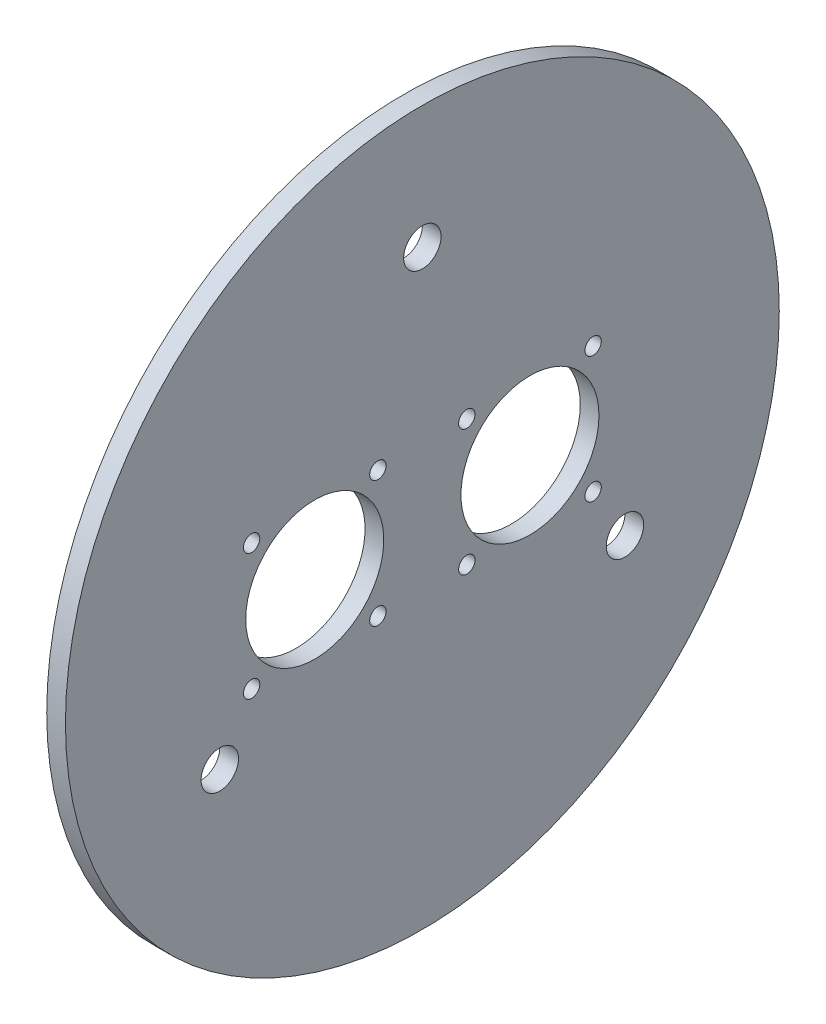
SolidWorks part; units mm, degrees
ref_plane "Front Plane" through (0, 0, 0) normal (0, 0, 1) x (1, 0, 0)
ref_plane "Top Plane" through (0, 0, 0) normal (0, 1, 0) x (1, 0, 0)
ref_plane "Right Plane" through (0, 0, 0) normal (1, 0, 0) x (0, 0, -1)
sketch "Sketch1" plane through (0, 0, 0) normal (1, 0, 0) x (0, 0, -1)
  line L0 (0, -76.29) -> (0, 76.29) construction
  line L1 (-76.29, 0) -> (76.29, 0) construction
  line L2 (23, 0) -> (36.4969, 13.4969) construction
  circle A0 centre (0, 0) radius 76.29
  circle A1 centre (0, 50) radius 4
  circle A2 centre (43.3013, -25) radius 4
  circle A3 centre (-43.3013, -25) radius 4
  circle A4 centre (23, 0) radius 14.75
  circle A5 centre (-23, 0) radius 14.75
  circle A6 centre (36.4969, 13.4969) radius 1.75
  circle A7 centre (36.4969, -13.4969) radius 1.75
  circle A8 centre (9.5031, -13.4969) radius 1.75
  circle A9 centre (9.5031, 13.4969) radius 1.75
  circle A10 centre (-36.4969, -13.4969) radius 1.75
  circle A11 centre (-9.5031, -13.4969) radius 1.75
  circle A12 centre (-9.5031, 13.4969) radius 1.75
  circle A13 centre (-36.4969, 13.4969) radius 1.75
  point P12 (0, 0)
  point P29 (23, 0)
  dimension "D1" = 152.58
  dimension "D2" = 8
  dimension "D5" = 29.5
  dimension "D7" = 3.5
  dimension "D3" = 50
  dimension "D4" = 3
  dimension "D6" = 23
  dimension "D8" = 19.0875
  dimension "D10" = 45
  dimension "D9" = 4
extrude "Boss-Extrude1" add sketch "Sketch1" along normal blind 4
